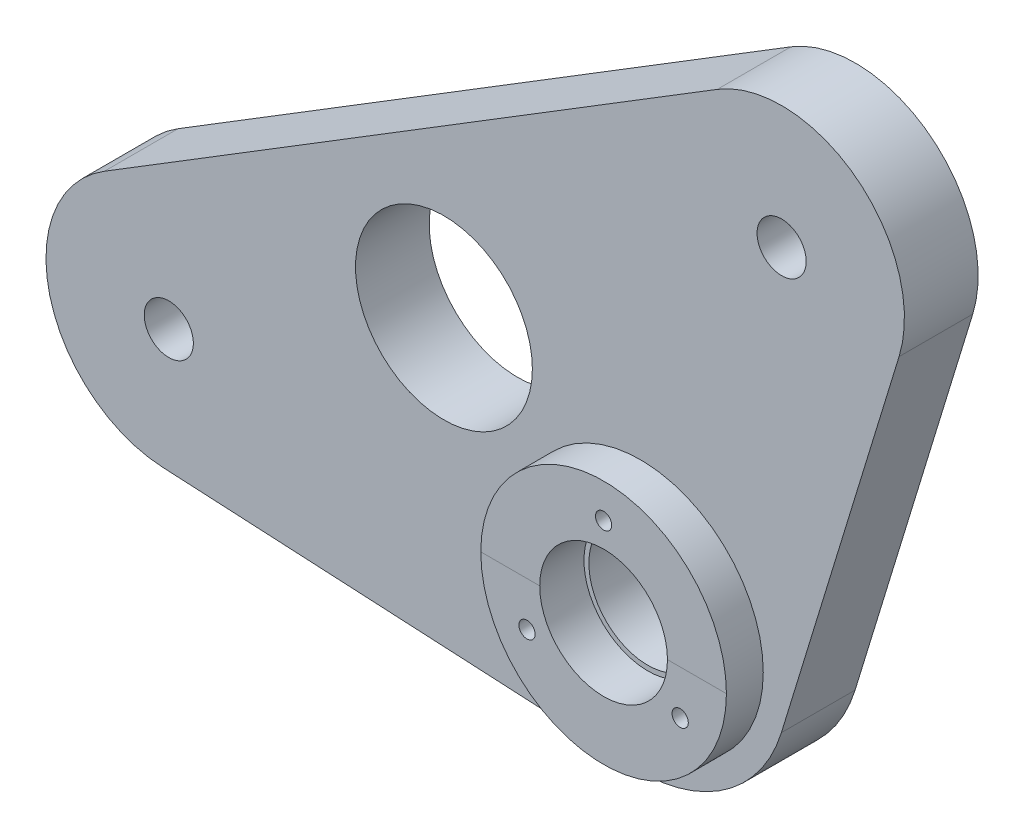
SolidWorks part; units mm, degrees
material "6061-T6 (SS)"
ref_plane "Front Plane" through (0, 0, 0) normal (0, 0, 1) x (1, 0, 0)
ref_plane "Top Plane" through (0, 0, 0) normal (0, 1, 0) x (1, 0, 0)
ref_plane "Right Plane" through (0, 0, 0) normal (1, 0, 0) x (0, 0, -1)
sketch "Layout_Reference" plane through (0, 0, 0) normal (0, 0, 1) x (1, 0, 0)
  line L0 (0, 0) -> (-96, 0) construction
  line L1 (0, 0) -> (28.736, 76.8) construction
  line L2 (-96, 0) -> (-232.8081, -375.877) construction
  line L3 (28.736, 76.8) -> (328.736, 76.8) construction
  dimension "D1" = 96
  dimension "D2" = 82
  dimension "D3" = 76.8
  dimension "D4" = 400
  dimension "D5" = 70
  dimension "D6" = 300
sketch "Rocker_Profile" plane through (0, 0, 0) normal (0, 0, 1) x (1, 0, 0)
  line L0 (-97.3021, -24.9661) -> (-1.5625, -29.9593)
  line L1 (28.6863, -8.7804) -> (52.6413, 69.483)
  line L2 (-109.1073, 21.2885) -> (15.6287, 98.0885)
  arc A0 (-1.5625, -29.9593) -> (28.6863, -8.7804) centre (0, 0) ccw
  arc A1 (52.6413, 69.483) -> (15.6287, 98.0885) centre (28.736, 76.8) ccw
  arc A2 (-109.1073, 21.2885) -> (-97.3021, -24.9661) centre (-96, 0) ccw
  dimension "D1" = 60
  dimension "D2" = 50
  dimension "D3" = 50
extrude "Baseline_Body" add sketch "Rocker_Profile" along normal mid plane 15
sketch "Sketch3" plane through (0, 0, 7.5) normal (0, 0, 1) x (1, 0, 0)
  circle A0 centre (-96, 0) radius 5
  circle A1 centre (28.736, 76.8) radius 5
  dimension "D1" = 10
  dimension "D2" = 10
extrude "Cut-Extrude1" cut sketch "Sketch3" against normal through all
sketch "Sketch4" plane through (0, 0, 0) normal (0, 0, 1) x (1, 0, 0)
  circle A0 centre (0, 0) radius 25
  dimension "D1" = 50
extrude "Boss-Extrude2" add sketch "Sketch4" along normal mid plane 30
sketch "Sketch5" plane through (0, 0, 15) normal (0, 0, 1) x (1, 0, 0)
  circle A0 centre (0, 0) radius 12
  dimension "D1" = 24
extrude "Cut-Extrude2" cut sketch "Sketch5" against normal through all
sketch "Sketch6" plane through (0, 0, 15) normal (0, 0, 1) x (1, 0, 0)
  circle A0 centre (0, 0) radius 13
  dimension "D1" = 26
extrude "Cut-Extrude3" cut sketch "Sketch6" against normal blind 9
sketch "Sketch7" plane through (0, 0, -15) normal (0, 0, -1) x (-1, 0, 0)
  circle A0 centre (0, 0) radius 13
  dimension "D1" = 26
extrude "Cut-Extrude4" cut sketch "Sketch7" against normal blind 9
hole_wizard "M4 Tapped Hole6" positions "Sketch13" profile "Sketch14" tap size "M4" standard "ISO"
sketch "Sketch13" plane through (0, 0, 15) normal (0, 0, 1) x (1, 0, 0)
  line L0 (0, 0) -> (0, 35.402) construction
  line L2 (0, 0) -> (31.5691, -18.2264) construction
  line L4 (0, 0) -> (-31.7239, -18.3158) construction
  circle A0 centre (0, 0) radius 18
  point P20 (0, 18)
  point P22 (15.5885, -9)
  point P24 (-15.5885, -9)
  dimension "D1" = 36
  dimension "D2" = 120
  dimension "D3" = 120
sketch "Sketch14" plane through (-15.5885, -9, 15) normal (1, 0, 0) x (0, -1, 0)
  line L0 (0, 0) -> (0, 9.9914)
  line L1 (0, 9.9914) -> (1.65, 9)
  line L2 (1.65, 9) -> (1.65, 0)
  line L5 (1.65, 0) -> (0, 0)
  line L10 (0, 9.9914) -> (-1.65, 9) construction
  line L11 (0, -6.35) -> (0, 107.95) construction
  dimension "Tap Drill Dia." = 3.3
  dimension "Tap Drill Depth" = 9
  dimension "Drill Angle" = 118
cosmetic thread "Hole Thread1" parameters "D1"=6, "D2"=4
cosmetic thread "Hole Thread2" parameters "D1"=6, "D2"=4
cosmetic thread "Hole Thread3" parameters "D1"=6, "D2"=4
hole_wizard "M4 Tapped Hole8" positions "Sketch15" profile "Sketch16" tap size "M4" standard "ISO"
sketch "Sketch15" plane through (0, 0, -15) normal (0, 0, -1) x (-1, 0, 0)
  line L0 (0, 0) -> (0, 31.1646) construction
  line L2 (0, 0) -> (31.1709, -17.9965) construction
  line L4 (0, 0) -> (-29.5586, -17.0657) construction
  circle A0 centre (0, 0) radius 18
  point P21 (0, 18)
  point P23 (15.5855, -8.9983)
  point P25 (-15.5885, -9)
  dimension "D1" = 36
  dimension "D2" = 120
  dimension "D3" = 120
sketch "Sketch16" plane through (15.5885, -9, -15) normal (1, 0, 0) x (0, 1, 0)
  line L0 (0, 0) -> (0, 9.9914)
  line L1 (0, 9.9914) -> (1.65, 9)
  line L2 (1.65, 9) -> (1.65, 0)
  line L5 (1.65, 0) -> (0, 0)
  line L10 (0, 9.9914) -> (-1.65, 9) construction
  line L11 (0, -6.35) -> (0, 107.95) construction
  dimension "Tap Drill Dia." = 3.3
  dimension "Tap Drill Depth" = 9
  dimension "Drill Angle" = 118
cosmetic thread "Hole Thread4" parameters "D1"=6, "D2"=4
cosmetic thread "Hole Thread5" parameters "D1"=6, "D2"=4
cosmetic thread "Hole Thread6" parameters "D1"=6, "D2"=4
split line "Split Line1"
ref_point "Point_Damper_Centre"
sketch "Sketch17" plane through (0, 0, 7.5) normal (0, 0, 1) x (1, 0, 0)
  circle A0 centre (-40, 30) radius 18
  dimension "D1" = 36
  dimension "D2" = 40
  dimension "D3" = 30
extrude "Lightening_Window" cut sketch "Sketch17" against normal through all both and the other way through all
